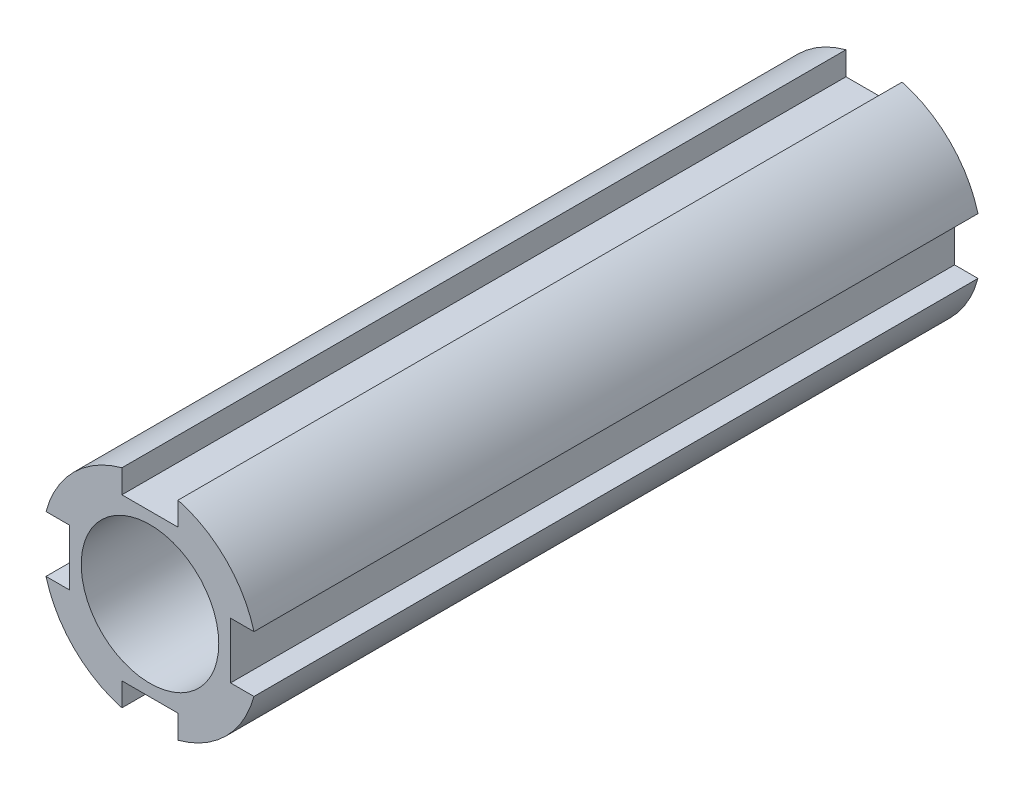
SolidWorks part; units mm, degrees
ref_plane "Front Plane" through (0, 0, 0) normal (0, 0, 1) x (1, 0, 0)
ref_plane "Top Plane" through (0, 0, 0) normal (0, 1, 0) x (1, 0, 0)
ref_plane "Right Plane" through (0, 0, 0) normal (1, 0, 0) x (0, 0, -1)
sketch "Sketch1" plane through (0, 0, 0) normal (0, 0, 1) x (1, 0, 0)
  circle A4 centre (0, 0) radius 5.95
  point P3 (-5.95, 0)
  point P8 (0, 5.95)
  point P13 (5.95, 0)
  point P18 (0, -5.95)
  dimension "D1" = 11.9
extrude "Boss-Extrude2" add sketch "Sketch1" along normal mid plane 40
sketch "Sketch8" plane through (0, 0, 20) normal (0, 0, 1) x (1, 0, 0)
  line L0 (1.1, 1.05) -> (2.4, 1.05)
  line L1 (-1, 2.35) -> (1.1, 2.35)
  line L2 (-1, 2.35) -> (-1, 1.05)
  line L3 (-1, -2.35) -> (1.1, -2.35)
  line L4 (1.1, 2.35) -> (1.1, 1.05)
  line L5 (-0.4348, 1) -> (0, 0) construction
  line L6 (-1, -2.35) -> (-0.4449, -1.0456) construction
  line L7 (-2.3, 1.05) -> (-1, 1.05)
  line L8 (-2.3, 1.05) -> (-2.3, -1.05)
  line L9 (-2.3, -1.05) -> (-1, -1.05)
  line L10 (2.4, 1.05) -> (2.4, -1.05)
  line L15 (1.1, -1.05) -> (1.1, -2.35)
  line L18 (-1, -1.05) -> (-1, -2.35)
  line L19 (1.1, -1.05) -> (2.4, -1.05)
  point P0 (0, 0)
  point P6 (0, 0)
  dimension "D1" = 4.7
  dimension "D2" = 4.7
  dimension "D3" = 2.1
  dimension "D4" = 2.1
extrude "Cut-Extrude1" cut sketch "Sketch8" against normal through all
sketch "Sketch9" plane through (0, 0, 20) normal (0, 0, 1) x (1, 0, 0)
  line L1 (-1.55, 7.45) -> (1.55, 7.45)
  line L2 (-1.55, 7.45) -> (-1.55, 4.45)
  line L3 (-1.55, 4.45) -> (1.55, 4.45)
  line L4 (1.55, 7.45) -> (1.55, 4.45)
  line L5 (-1.55, 7.45) -> (1.55, 4.45) construction
  line L6 (-1.55, 4.45) -> (1.55, 7.45) construction
  line L7 (4.45, 1.55) -> (7.45, 1.55)
  line L8 (4.45, 1.55) -> (4.45, -1.55)
  line L9 (4.45, -1.55) -> (7.45, -1.55)
  line L10 (7.45, 1.55) -> (7.45, -1.55)
  line L11 (4.45, 1.55) -> (7.45, -1.55) construction
  line L12 (4.45, -1.55) -> (7.45, 1.55) construction
  line L13 (-1.55, -4.45) -> (1.55, -4.45)
  line L14 (-1.55, -4.45) -> (-1.55, -7.45)
  line L15 (-1.55, -7.45) -> (1.55, -7.45)
  line L16 (1.55, -4.45) -> (1.55, -7.45)
  line L17 (-1.55, -4.45) -> (1.55, -7.45) construction
  line L18 (-1.55, -7.45) -> (1.55, -4.45) construction
  line L19 (-7.45, 1.55) -> (-4.45, 1.55)
  line L20 (-7.45, 1.55) -> (-7.45, -1.55)
  line L21 (-7.45, -1.55) -> (-4.45, -1.55)
  line L22 (-4.45, 1.55) -> (-4.45, -1.55)
  line L23 (-7.45, 1.55) -> (-4.45, -1.55) construction
  line L24 (-7.45, -1.55) -> (-4.45, 1.55) construction
  circle A0 centre (0, 0) radius 5.95
  point P3 (0, 5.95)
  point P8 (5.95, 0)
  point P13 (0, -5.95)
  point P18 (-5.95, 0)
  point P23 (1.55, 5.95)
  circle M17 centre (0, 0) radius 5.95
  dimension "D1" = 1.5
  dimension "D4" = 11.9
  dimension "D2" = 1.5
  dimension "D3" = 1.5
  dimension "D5" = 1.5
  dimension "D6" = 3.1
  dimension "D7" = 3.1
  dimension "D8" = 3.1
  dimension "D9" = 3.1
extrude "Cut-Extrude3" cut sketch "Sketch9" against normal through all contours L4 L2 L3 M17 | L8 L9 L7 M17 | L22 L19 L21 M17 | L16 L13 L14 M17
sketch "Sketch10" plane through (0, 0, 20) normal (0, 0, 1) x (1, 0, 0)
  circle A0 centre (0, 0) radius 3.8
  dimension "D1" = 7.6
extrude "Cut-Extrude4" cut sketch "Sketch10" against normal blind 8
mirror "Mirror1" about plane through (0, 0, 0) normal (0, 0, 1) of "Cut-Extrude4"
fillet "Fillet2" radius 0.25 4 edges at (-1, -1.05, 0) (1.1, -1.05, 0) (1.1, 1.05, 0) (-1, 1.05, 0)
